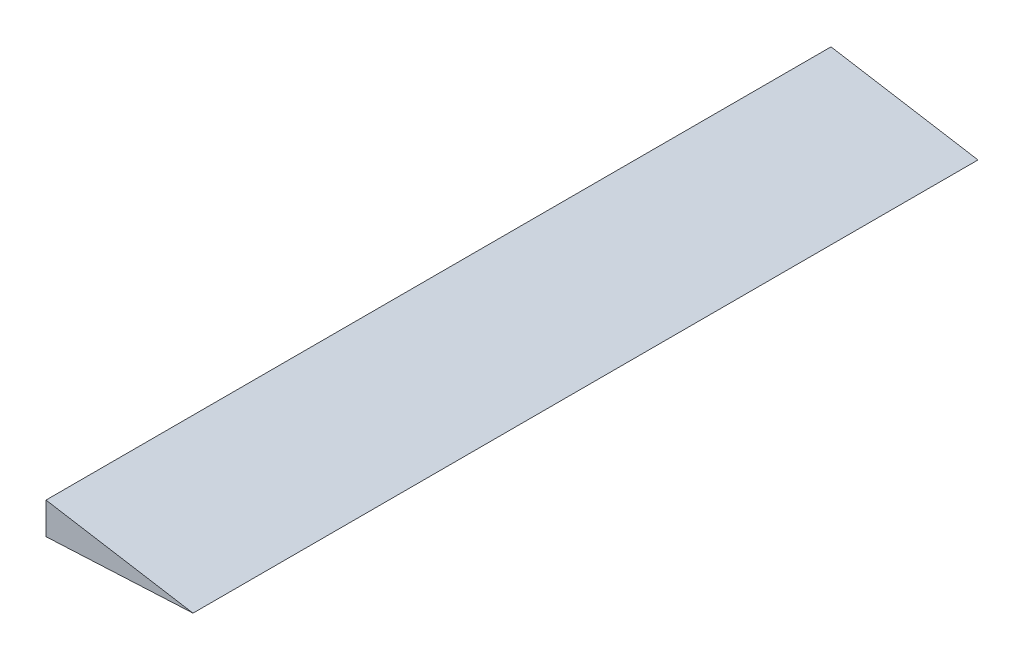
SolidWorks part; units mm, degrees
material "Balsa"
ref_plane "Front Plane" through (0, 0, 0) normal (0, 0, 1) x (1, 0, 0)
ref_plane "Top Plane" through (0, 0, 0) normal (0, 1, 0) x (1, 0, 0)
ref_plane "Right Plane" through (0, 0, 0) normal (1, 0, 0) x (0, 0, -1)
sketch "Sketch1" plane through (0, 0, 0) normal (0, 0, 1) x (1, 0, 0)
  line L0 (306.8496, -2.5161) -> (306.8496, 8.4499) construction
  line L1 (306.8496, -2.5161) -> (306.8496, 8.4499)
  line L2 (306.8496, 8.4499) -> (357.6496, 0)
  line L3 (306.8496, -2.5161) -> (357.6496, 0)
  spline S0 degree 3 poles (354.9573, 0.0431) (358.3317, -0.0432) (354.9981, 0.2938) (352.3707, 0.8024) (346.1763, 1.8676) (338.7813, 3.2655) (329.3081, 4.8919) (318.2482, 6.6648) (305.5952, 8.6507) (291.564, 10.8193) (276.34, 13.1505) (260.1392, 15.5903) (243.1815, 18.0913) (225.699, 20.6027) (207.9209, 23.0318) (190.087, 25.3152) (172.4086, 27.3328) (155.0467, 28.9096) (138.1258, 29.947) (121.7437, 30.3922) (105.9899, 30.2108) (90.9433, 29.4155) (76.6903, 28.0308) (63.3272, 26.1868) (50.9728, 23.9485) (39.7523, 21.3791) (29.7714, 18.545) (21.1318, 15.5018) (13.8914, 12.3237) (8.1391, 9.1075) (3.8158, 5.9031) (1.1802, 2.9693) (-0.4877, -0.018) (1.2572, -2.9285) (4.805, -4.6528) (9.8754, -6.6365) (16.78, -8.2511) (25.3535, -9.7017) (35.5828, -10.8813) (47.3622, -11.8027) (60.5842, -12.4624) (75.1117, -12.8607) (90.7897, -13.0132) (107.4435, -12.9137) (124.9052, -12.5651) (143.0256, -11.8868) (161.6617, -10.9405) (180.6424, -9.8572) (199.7442, -8.7119) (218.721, -7.5525) (237.3263, -6.4253) (255.3201, -5.3536) (272.4652, -4.367) (288.5372, -3.4753) (303.3148, -2.6922) (316.6121, -2.0207) (328.2104, -1.4385) (338.1246, -0.9102) (345.8395, -0.4061) (352.2525, -0.129) (354.9573, 0.0431) (358.3317, -0.0432) (354.9981, 0.2938) knots -0.015092 -0.006889 -0.001754 0 0.001748 0.006827 0.01488 0.025572 0.038694 0.054171 0.071834 0.091435 0.112685 0.135293 0.158944 0.183315 0.20807 0.232879 0.257399 0.281384 0.304706 0.327241 0.348897 0.369607 0.389308 0.407886 0.425177 0.441027 0.4553 0.467904 0.478752 0.487814 0.49509 0.500617 0.504451 0.507804 0.513091 0.520546 0.530249 0.542214 0.556382 0.572656 0.590895 0.610925 0.632536 0.655496 0.679547 0.704499 0.730211 0.756436 0.782837 0.809062 0.834776 0.859641 0.883338 0.905541 0.925965 0.944326 0.960366 0.973929 0.984908 0.993111 0.998246 1 1.001748 1.006827 1.01488 only from (357.6496, 0) to (357.6496, 0) construction
  spline S1 degree 3 poles (354.9573, 0.0431) (358.3317, -0.0432) (354.9981, 0.2938) (352.3707, 0.8024) (346.1763, 1.8676) (338.7813, 3.2655) (329.3081, 4.8919) (318.2482, 6.6648) (305.5952, 8.6507) (291.564, 10.8193) (276.34, 13.1505) (260.1392, 15.5903) (243.1815, 18.0913) (225.699, 20.6027) (207.9209, 23.0318) (190.087, 25.3152) (172.4086, 27.3328) (155.0467, 28.9096) (138.1258, 29.947) (121.7437, 30.3922) (105.9899, 30.2108) (90.9433, 29.4155) (76.6903, 28.0308) (63.3272, 26.1868) (50.9728, 23.9485) (39.7523, 21.3791) (29.7714, 18.545) (21.1318, 15.5018) (13.8914, 12.3237) (8.1391, 9.1075) (3.8158, 5.9031) (1.1802, 2.9693) (-0.4877, -0.018) (1.2572, -2.9285) (4.805, -4.6528) (9.8754, -6.6365) (16.78, -8.2511) (25.3535, -9.7017) (35.5828, -10.8813) (47.3622, -11.8027) (60.5842, -12.4624) (75.1117, -12.8607) (90.7897, -13.0132) (107.4435, -12.9137) (124.9052, -12.5651) (143.0256, -11.8868) (161.6617, -10.9405) (180.6424, -9.8572) (199.7442, -8.7119) (218.721, -7.5525) (237.3263, -6.4253) (255.3201, -5.3536) (272.4652, -4.367) (288.5372, -3.4753) (303.3148, -2.6922) (316.6121, -2.0207) (328.2104, -1.4385) (338.1246, -0.9102) (345.8395, -0.4061) (352.2525, -0.129) (354.9573, 0.0431) (358.3317, -0.0432) (354.9981, 0.2938) knots -0.015092 -0.006889 -0.001754 0 0.001748 0.006827 0.01488 0.025572 0.038694 0.054171 0.071834 0.091435 0.112685 0.135293 0.158944 0.183315 0.20807 0.232879 0.257399 0.281384 0.304706 0.327241 0.348897 0.369607 0.389308 0.407886 0.425177 0.441027 0.4553 0.467904 0.478752 0.487814 0.49509 0.500617 0.504451 0.507804 0.513091 0.520546 0.530249 0.542214 0.556382 0.572656 0.590895 0.610925 0.632536 0.655496 0.679547 0.704499 0.730211 0.756436 0.782837 0.809062 0.834776 0.859641 0.883338 0.905541 0.925965 0.944326 0.960366 0.973929 0.984908 0.993111 0.998246 1 1.001748 1.006827 1.01488 only from (357.6496, 0) to (357.6496, 0)
sketch "Sketch2" plane through (0, 0, -761.9997) normal (0, 0, -1) x (-1, 0, 0)
  line L0 (-306.8496, -2.5161) -> (-306.8496, 8.4499) construction
  line L1 (-306.8496, -2.5161) -> (-357.6496, 0) construction
  line L2 (-306.8496, 8.4499) -> (-357.6496, 0) construction
  line L3 (-306.8496, -2.5161) -> (-306.8496, 8.4499)
  line L4 (-306.8496, -2.5161) -> (-357.6496, 0)
  line L5 (-306.8496, 8.4499) -> (-357.6496, 0)
extrude "Boss-Extrude2" add sketch "Sketch2" against normal blind 271.272
sketch "Sketch3" plane through (306.8496, 0, 0) normal (-1, 0, 0) x (0, 0, 1)
  line L0 (-761.9997, -2.5161) -> (-761.9997, 8.4499) construction
  line L1 (-490.7277, -2.5161) -> (-490.7277, 8.4499) construction
  point P0 (-761.9997, 2.9669)
  point P1 (-490.7277, 2.9669)
